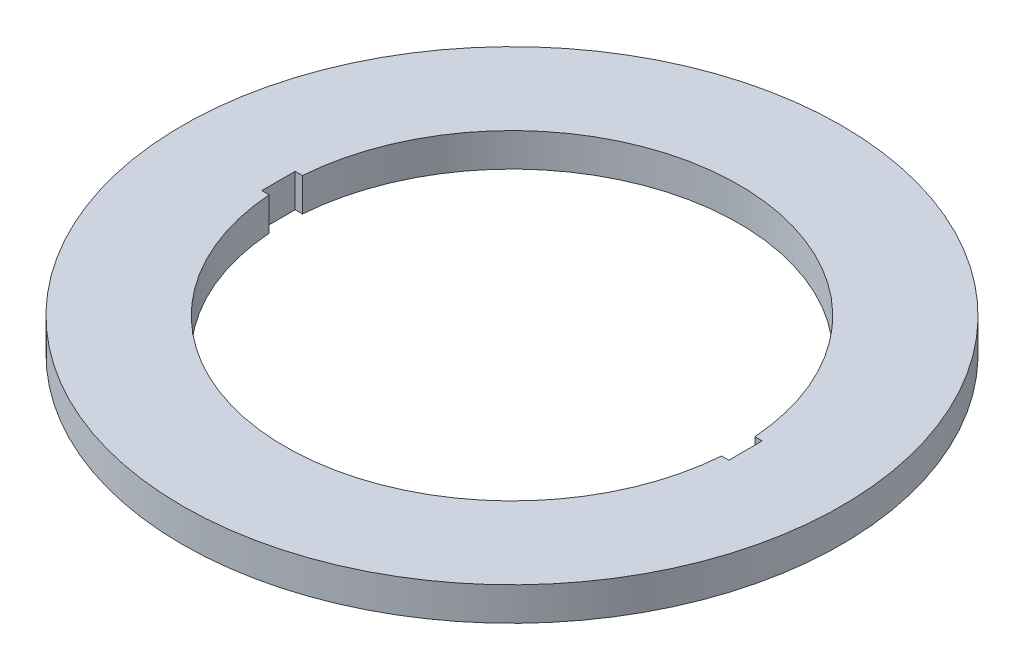
SolidWorks part; units mm, degrees
material "Cedar"
ref_plane "Front Plane" through (0, 0, 0) normal (0, 0, 1) x (1, 0, 0)
ref_plane "Top Plane" through (0, 0, 0) normal (0, 1, 0) x (1, 0, 0)
ref_plane "Right Plane" through (0, 0, 0) normal (1, 0, 0) x (0, 0, -1)
sketch "Sketch1" plane through (0, 0, 0) normal (0, 1, 0) x (1, 0, 0)
  line L0 (-22.225, 0) -> (22.225, 0) construction
  line L1 (-22.225, 1.5875) -> (-21.5316, 1.5875)
  line L2 (-22.225, 1.5875) -> (-22.225, -1.5875)
  line L3 (-22.225, -1.5875) -> (-21.5316, -1.5875)
  line L5 (21.5316, 1.5875) -> (22.225, 1.5875)
  line L7 (21.5316, -1.5875) -> (22.225, -1.5875)
  line L8 (22.225, 1.5875) -> (22.225, -1.5875)
  circle A0 centre (0, 0) radius 31.369
  arc A1 (-21.5316, -1.5875) -> (21.5316, -1.5875) centre (0, 0) ccw
  arc A2 (21.5316, 1.5875) -> (-21.5316, 1.5875) centre (0, 0) ccw
  dimension "D1" = 62.738
  dimension "D2" = 43.18
  dimension "D3" = 44.45
  dimension "D4" = 3.175
extrude "Boss-Extrude1" add sketch "Sketch1" along normal blind 3.175
